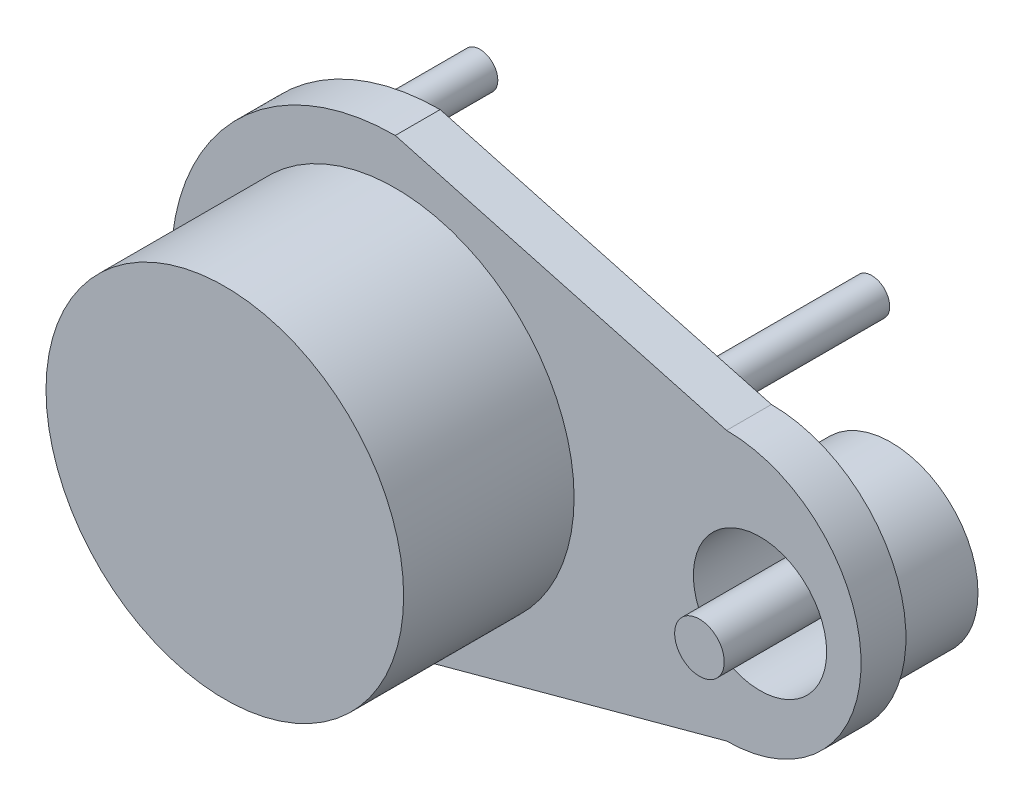
SolidWorks part; units mm, degrees
ref_plane "Front Plane" through (0, 0, 0) normal (0, 0, 1) x (1, 0, 0)
ref_plane "Top Plane" through (0, 0, 0) normal (0, 1, 0) x (1, 0, 0)
ref_plane "Right Plane" through (0, 0, 0) normal (1, 0, 0) x (0, 0, -1)
ref_plane "Plane1" through (0, 0, 0.75) normal (0, 0, 1) x (1, 0, 0)
sketch "Sketch1" plane through (0, 0, 0.75) normal (0, 0, 1) x (1, 0, 0)
  line L0 (0, -3.75) -> (5.5393, -2.2492)
  line L1 (5.5393, 2.2492) -> (0, 3.75)
  arc A0 (0, 3.75) -> (0, -3.75) centre (0, 0) ccw
  arc A1 (5.5393, -2.2492) -> (5.5393, 2.2492) centre (5.5393, 0) ccw
extrude "Boss-Extrude1" add sketch "Sketch1" against normal blind 0.75
sketch "Sketch2" plane through (0, 0, 0) normal (0, 0, -1) x (-1, 0, 0)
  circle A0 centre (-6.1899, -0.1013) radius 1.4535
extrude "Boss-Extrude2" add sketch "Sketch2" along normal blind 1.35
hole_wizard "M2 Clearance Hole1" positions "Sketch4" profile "Sketch3" hole size "M2" standard "ANSI Metric"
sketch "Sketch4" plane through (0, 0, 0.75) normal (0, 0, 1) x (1, 0, 0)
  point P0 (6.0988, -0.1252)
sketch "Sketch3" plane through (6.0988, -0.1252, 0.75) normal (1, 0, 0) x (0, -1, 0)
  line L0 (0, 0) -> (0, 2.1)
  line L1 (0, 2.1) -> (1.1141, 2.1)
  line L2 (1.1141, 2.1) -> (1.1141, 0)
  line L5 (1.1141, 0) -> (0, 0)
  line L11 (0, -6.35) -> (0, 107.95) construction
  dimension "Thru Hole Dia." = 2.2282
  dimension "Thru Hole Depth" = 2.1
ref_plane "Plane2" through (0, 0, 0) normal (0, 0, -1) x (-1, 0, 0)
sketch "Sketch5" plane through (0, 0, 0) normal (0, 0, -1) x (-1, 0, 0)
  circle A0 centre (-6.1361, -0.0739) radius 0.4144
extrude "Boss-Extrude3" add sketch "Sketch5" against normal blind 1.8
sketch "Sketch6" plane through (0, 0, 0) normal (0, 0, -1) x (-1, 0, 0)
  circle A0 centre (-4.1941, -1.1939) radius 0.3
extrude "Boss-Extrude4" add sketch "Sketch6" along normal blind 3
sketch "Sketch7" plane through (0, 0, 0) normal (0, 0, -1) x (-1, 0, 0)
  circle A0 centre (2.3221, -1.1939) radius 0.3
extrude "Boss-Extrude5" add sketch "Sketch7" along normal blind 3
sketch "Sketch8" plane through (0, 0, 0) normal (0, 0, -1) x (-1, 0, 0)
  circle A0 centre (-4.217, 1.6561) radius 0.3
extrude "Boss-Extrude6" add sketch "Sketch8" along normal blind 3
sketch "Sketch9" plane through (0, 0, 0) normal (0, 0, -1) x (-1, 0, 0)
  circle A0 centre (2.3355, 1.6561) radius 0.3
extrude "Boss-Extrude7" add sketch "Sketch9" along normal blind 3
ref_plane "Plane3" through (0, 0, 0) normal (0, -1, 0) x (1, 0, 0)
sketch "Sketch10" plane through (0, 0, 0) normal (0, -1, 0) x (1, 0, 0)
  line L0 (2.99, 3.6) -> (0, 3.6)
  line L1 (0, 3.6) -> (0, 0.75)
  line L2 (0, 0.75) -> (2.99, 0.75)
  line L3 (2.99, 0.75) -> (2.99, 3.6)
  line L4 (0, 3.6) -> (0, 0.75) construction
revolve "Revolve1" add sketch "Sketch10" angle 360 about L4
